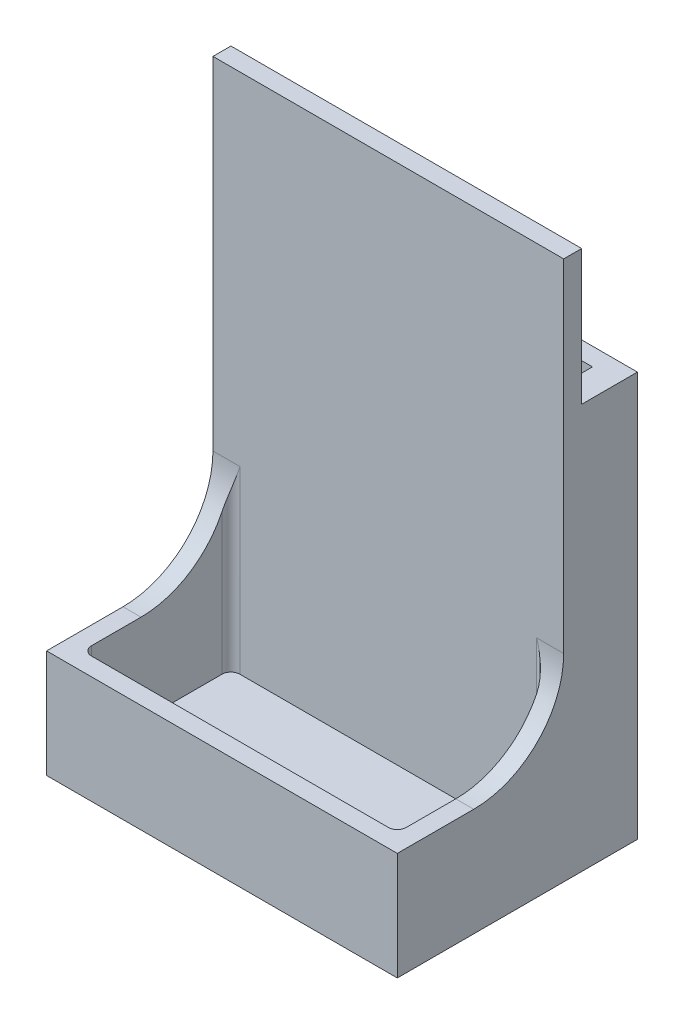
SolidWorks part; units mm, degrees
ref_plane "Front Plane" through (0, 0, 0) normal (0, 0, 1) x (1, 0, 0)
ref_plane "Top Plane" through (0, 0, 0) normal (0, 1, 0) x (1, 0, 0)
ref_plane "Right Plane" through (0, 0, 0) normal (1, 0, 0) x (0, 0, -1)
sketch "Sketch1" plane through (0, 0, 0) normal (0, 1, 0) x (1, 0, 0)
  line L0 (-19.5, 10.25) -> (19.5, 10.25)
  line L1 (-17.5, 8.25) -> (17.5, 8.25) construction
  line L2 (-17.5, 8.25) -> (-17.5, -8.25) construction
  line L3 (-17.5, -8.25) -> (17.5, -8.25) construction
  line L4 (17.5, 8.25) -> (17.5, -8.25) construction
  line L5 (0, -8.25) -> (0, 8.25) construction
  line L6 (-17.5, 0) -> (17.5, 0) construction
  line L7 (19.5, 10.25) -> (19.5, -10.25)
  line L8 (-19.5, -10.25) -> (19.5, -10.25)
  line L9 (-19.5, 10.25) -> (-19.5, -10.25)
  point P4 (0, 0)
  point P84 (0, 0)
  dimension "D1" = 35
  dimension "D2" = 16.5
  dimension "D3" = 2
extrude "Boss-Extrude1" add sketch "Sketch1" along normal blind 2
sketch "Sketch2" plane through (0, 2, 0) normal (0, 1, 0) x (1, 0, 0)
  line L4 (-17.5, -8.25) -> (17.5, -8.25)
  line L5 (17.5, -8.25) -> (17.5, 8.25)
  line L6 (17.5, 8.25) -> (-17.5, 8.25)
  line L7 (-17.5, 8.25) -> (-17.5, -8.25)
  line L8 (-19.5, -10.25) -> (19.5, -10.25)
  line L9 (-19.5, 10.25) -> (-19.5, -10.25)
  line L10 (19.5, 10.25) -> (-19.5, 10.25)
  line L11 (19.5, -10.25) -> (19.5, 10.25)
  line L12 (-19.5, -10.25) -> (19.5, -10.25)
  line L13 (-19.5, 10.25) -> (-19.5, -10.25)
  line L14 (19.5, 10.25) -> (-19.5, 10.25)
  line L15 (19.5, -10.25) -> (19.5, 10.25)
  dimension "D1" = 0
  dimension "D2" = 2
extrude "Boss-Extrude2" add sketch "Sketch2" along normal blind 10
ref_plane "Plane1" through (0, 60, 0) normal (0, -1, 0) x (-1, 0, 0)
sketch "Sketch3" plane through (0, 12, 0) normal (0, 1, 0) x (1, 0, 0)
  line L0 (-19.5, 10.25) -> (19.5, 10.25)
  line L1 (19.5, 10.25) -> (19.5, 8.25)
  line L2 (19.5, -10.25) -> (19.5, 10.25) construction
  line L3 (19.5, 8.25) -> (-19.5, 8.25)
  line L4 (-19.5, 10.25) -> (-19.5, -10.25) construction
  line L5 (-19.5, 8.25) -> (-19.5, 10.25)
  line L6 (17.5, 8.25) -> (-17.5, 8.25) construction
extrude "Boss-Extrude3" add sketch "Sketch3" along normal up to surface (48 mm away) up to plane "Plane1"
fillet "Fillet1" radius 10 2 edges at (-18.5, 12, -8.25) (18.5, 12, -8.25)
fillet "Fillet2" radius 1 4 edges at (-17.5, 7, 8.25) (-17.5, 12, -8.25) (17.5, 7, 8.25) (17.5, 12, -8.25)
sketch "Sketch4" plane through (0, 0, 0) normal (0, -1, 0) x (1, 0, 0)
  line L0 (-19.5, -10.25) -> (-19.5, -16.45)
  line L1 (-19.5, -16.45) -> (-11.5, -16.45)
  line L2 (-11.5, -16.45) -> (-11.5, -14.45)
  line L3 (-11.5, -14.45) -> (-16.5, -14.45)
  line L4 (-16.5, -14.45) -> (-16.5, -11.25)
  line L5 (-16.5, -11.25) -> (-8.5, -11.25)
  line L6 (-8.5, -11.25) -> (-6.7679, -10.25)
  line L7 (19.5, -10.25) -> (-19.5, -10.25) construction
  line L8 (-6.7679, -10.25) -> (-19.5, -10.25)
  point P3 (-6.8715, -12.25)
  dimension "D1" = 30
  dimension "D2" = 3
  dimension "D3" = 2
  dimension "D4" = 1
  dimension "D5" = 8
  dimension "D6" = 3.2
  dimension "D7" = 8
extrude "Boss-Extrude4" add sketch "Sketch4" against normal blind 45
ref_plane "Plane4" through (0, 0, 0) normal (-1, 0, 0) x (0, 0, 1)
mirror "Mirror2" about plane through (0, 0, 0) normal (-1, 0, 0) of "Boss-Extrude4"
